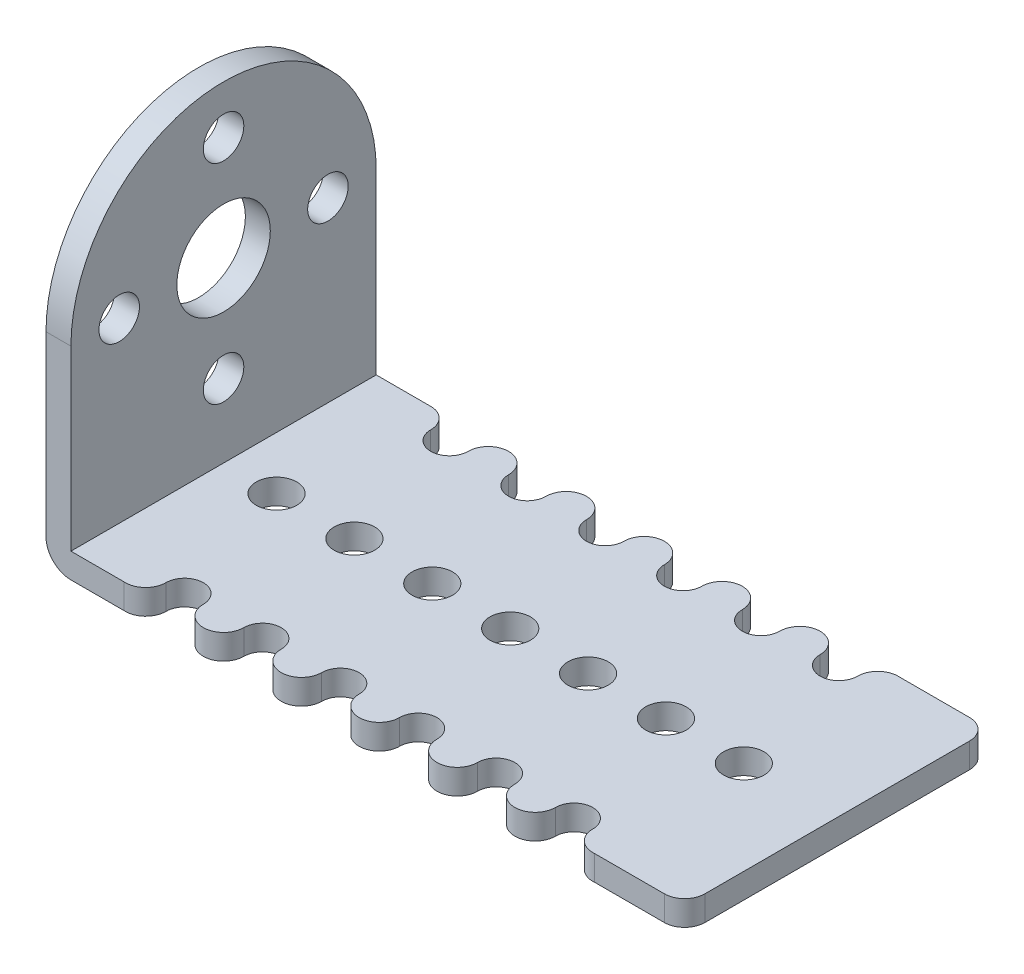
SolidWorks part; units mm, degrees
ref_plane "Front Plane" through (0, 0, 0) normal (0, 0, 1) x (1, 0, 0)
ref_plane "Top Plane" through (0, 0, 0) normal (0, 1, 0) x (1, 0, 0)
ref_plane "Right Plane" through (0, 0, 0) normal (1, 0, 0) x (0, 0, -1)
ref_plane "Plane1" through (0, 0, 0) normal (0, -1, 0) x (1, 0, 0)
sketch "Sketch1" plane through (0, 0, 0) normal (0, -1, 0) x (1, 0, 0)
  line L0 (44.704, -12.446) -> (44.704, 12.446)
  line L1 (6.35, 12.446) -> (6.35, -12.446)
  arc A0 (42.926, -10.795) -> (44.704, -12.446) centre (44.5815, -10.795) ccw
  arc A1 (44.704, 12.446) -> (42.926, 10.795) centre (44.5815, 10.795) ccw
  arc A2 (42.926, 10.795) -> (39.878, 10.795) centre (41.402, 10.795) cw
  arc A3 (39.878, 10.795) -> (36.576, 10.795) centre (38.227, 10.795) ccw
  arc A4 (36.576, 10.795) -> (33.528, 10.795) centre (35.052, 10.795) cw
  arc A5 (33.528, 10.795) -> (30.226, 10.795) centre (31.877, 10.795) ccw
  arc A6 (30.226, 10.795) -> (27.178, 10.795) centre (28.702, 10.795) cw
  arc A7 (27.178, 10.795) -> (23.876, 10.795) centre (25.527, 10.795) ccw
  arc A8 (23.876, 10.795) -> (20.828, 10.795) centre (22.352, 10.795) cw
  arc A9 (20.828, 10.795) -> (17.526, 10.795) centre (19.177, 10.795) ccw
  arc A10 (17.526, 10.795) -> (14.478, 10.795) centre (16.002, 10.795) cw
  arc A11 (14.478, 10.795) -> (11.176, 10.795) centre (12.827, 10.795) ccw
  arc A12 (11.176, 10.795) -> (8.128, 10.795) centre (9.652, 10.795) cw
  arc A13 (8.128, 10.795) -> (6.35, 12.446) centre (6.4725, 10.795) ccw
  arc A14 (6.35, -12.446) -> (8.128, -10.795) centre (6.4725, -10.795) ccw
  arc A15 (8.128, -10.795) -> (11.176, -10.795) centre (9.652, -10.795) cw
  arc A16 (11.176, -10.795) -> (14.478, -10.795) centre (12.827, -10.795) ccw
  arc A17 (14.478, -10.795) -> (17.526, -10.795) centre (16.002, -10.795) cw
  arc A18 (17.526, -10.795) -> (20.828, -10.795) centre (19.177, -10.795) ccw
  arc A19 (20.828, -10.795) -> (23.876, -10.795) centre (22.352, -10.795) cw
  arc A20 (23.876, -10.795) -> (27.178, -10.795) centre (25.527, -10.795) ccw
  arc A21 (27.178, -10.795) -> (30.226, -10.795) centre (28.702, -10.795) cw
  arc A22 (30.226, -10.795) -> (33.528, -10.795) centre (31.877, -10.795) ccw
  arc A23 (33.528, -10.795) -> (36.576, -10.795) centre (35.052, -10.795) cw
  arc A24 (36.576, -10.795) -> (39.878, -10.795) centre (38.227, -10.795) ccw
  arc A25 (39.878, -10.795) -> (42.926, -10.795) centre (41.402, -10.795) cw
extrude "Boss-Extrude1" add sketch "Sketch1" against normal blind 2.032
sketch "Sketch2" plane through (44.704, 0, 0) normal (1, 0, 0) x (0, 0, -1)
  line L0 (12.446, 0) -> (-12.446, 0)
  line L1 (-12.446, 0) -> (-12.446, 2.032)
  line L2 (-12.446, 2.032) -> (12.446, 2.032)
  line L3 (12.446, 2.032) -> (12.446, 0)
extrude "Boss-Extrude2" add sketch "Sketch2" along normal blind 7.366
sketch "Sketch3" plane through (6.35, 0, 0) normal (-1, 0, 0) x (0, 0, 1)
  line L0 (-12.446, 2.032) -> (12.446, 2.032)
  line L1 (12.446, 2.032) -> (12.446, 0)
  line L2 (12.446, 0) -> (-12.446, 0)
  line L3 (-12.446, 0) -> (-12.446, 2.032)
extrude "Boss-Extrude3" add sketch "Sketch3" along normal blind 4.318
sketch "Sketch4" plane through (2.032, 0, 0) normal (-1, 0, 0) x (0, 0, 1)
  line L0 (-12.446, 0) -> (-12.446, 16.51)
  line L1 (12.446, 16.51) -> (12.446, 0)
  line L2 (12.446, 0) -> (-12.446, 0)
  arc A0 (-12.446, 16.51) -> (12.446, 16.51) centre (0, 16.51) cw
extrude "Boss-Extrude4" add sketch "Sketch4" along normal blind 2.032
hole_wizard "M7 Clearance Hole1" positions "Sketch6" profile "Sketch5" hole size "M7" standard "ANSI Metric"
sketch "Sketch6" plane through (2.032, 0, 0) normal (1, 0, 0) x (0, 0, -1)
  point P0 (0, 16.51)
sketch "Sketch5" plane through (2.032, 16.51, 0) normal (0, 1, 0) x (0, 0, -1)
  line L0 (0, 0) -> (0, 2.032)
  line L1 (0, 2.032) -> (3.81, 2.032)
  line L2 (3.81, 2.032) -> (3.81, 0)
  line L5 (3.81, 0) -> (0, 0)
  line L11 (0, -6.35) -> (0, 107.95) construction
  dimension "Thru Hole Dia." = 7.62
  dimension "Thru Hole Depth" = 2.032
hole_wizard "M3 Clearance Hole1" positions "Sketch8" profile "Sketch7" hole size "M3" standard "ANSI Metric"
sketch "Sketch8" plane through (2.032, 0, 0) normal (1, 0, 0) x (0, 0, -1)
  point P0 (0, 25.019)
  point P1 (0, 8.001)
  point P2 (-8.509, 16.51)
  point P3 (8.509, 16.51)
sketch "Sketch7" plane through (2.032, 25.019, 0) normal (0, 1, 0) x (0, 0, -1)
  line L0 (0, 0) -> (0, 2.032)
  line L1 (0, 2.032) -> (1.651, 2.032)
  line L2 (1.651, 2.032) -> (1.651, 0)
  line L5 (1.651, 0) -> (0, 0)
  line L11 (0, -6.35) -> (0, 107.95) construction
  dimension "Thru Hole Dia." = 3.302
  dimension "Thru Hole Depth" = 2.032
hole_wizard "M3 Clearance Hole2" positions "Sketch10" profile "Sketch9" hole size "M3" standard "ANSI Metric"
sketch "Sketch10" plane through (0, 0, 0) normal (0, -1, 0) x (-1, 0, 0)
  point P0 (-38.1, 0)
  point P1 (-25.4, 0)
  point P2 (-12.7, 0)
  point P3 (-6.35, 0)
  point P4 (-19.05, 0)
  point P5 (-31.75, 0)
  point P6 (-44.45, 0)
sketch "Sketch9" plane through (38.1, 0, 0) normal (1, 0, 0) x (0, 0, -1)
  line L0 (0, 0) -> (0, 28.956)
  line L1 (0, 28.956) -> (1.651, 28.956)
  line L2 (1.651, 28.956) -> (1.651, 0)
  line L5 (1.651, 0) -> (0, 0)
  line L11 (0, -6.35) -> (0, 107.95) construction
  dimension "Thru Hole Dia." = 3.302
  dimension "Thru Hole Depth" = 28.956
fillet "Fillet1" radius 1.6555 2 edges at (52.07, 1.016, 12.446) (52.07, 1.016, -12.446)
fillet "Fillet2" radius 2.032 1 edges at (0, 0, 0)
